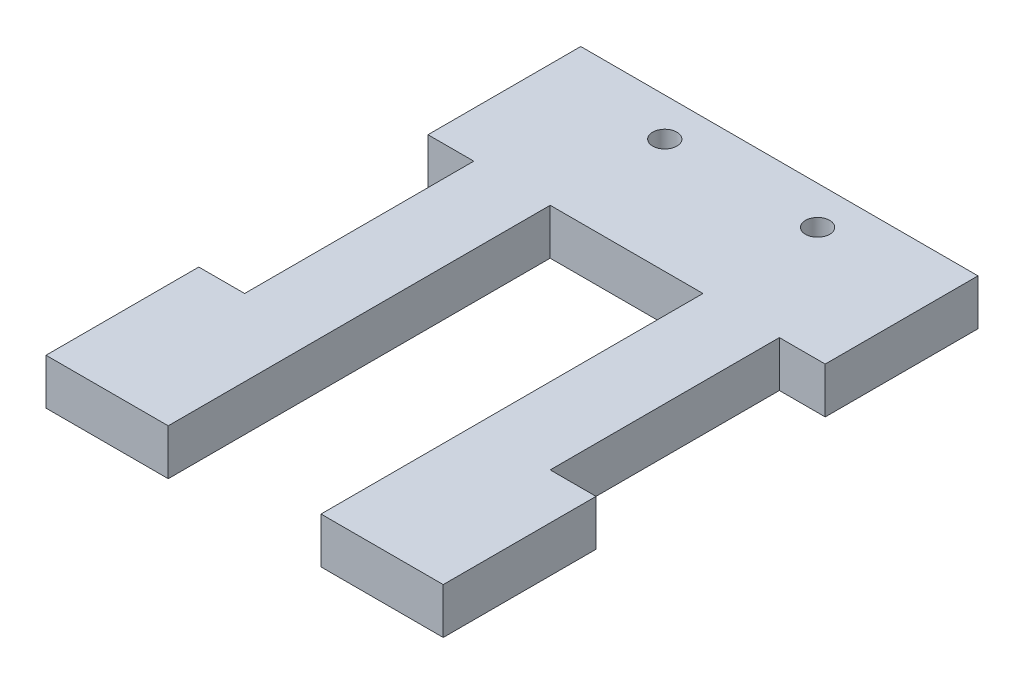
SolidWorks part; units mm, degrees
ref_plane "Front Plane" through (0, 0, 0) normal (0, 0, 1) x (1, 0, 0)
ref_plane "Top Plane" through (0, 0, 0) normal (0, 1, 0) x (1, 0, 0)
ref_plane "Right Plane" through (0, 0, 0) normal (1, 0, 0) x (0, 0, -1)
sketch "Sketch1" plane through (0, 0, 0) normal (0, 1, 0) x (1, 0, 0)
  line L0 (-10, -35) -> (-10, 35)
  line L1 (-20, 35) -> (20, 35)
  line L2 (-20, 35) -> (-20, -35)
  line L3 (-20, -35) -> (20, -35)
  line L4 (20, 35) -> (20, -35)
  line L5 (-20, 35) -> (20, -35) construction
  line L6 (-20, -35) -> (20, 35) construction
  line L7 (10, -35) -> (10, 35)
  line L8 (-20, 15) -> (20, 15)
  line L9 (-20, 0) -> (20, 0) construction
  line L10 (-20, 15) -> (-26, 15)
  line L11 (-20, 15) -> (-20, 35)
  line L12 (-20, 35) -> (-26, 35)
  line L13 (-26, 15) -> (-26, 35)
  line L14 (-26, -15) -> (-26, -35)
  line L15 (-20, -35) -> (-26, -35)
  line L16 (-20, -15) -> (-20, -35)
  line L17 (-20, -15) -> (-26, -15)
  line L18 (0, 35) -> (0, 15)
  line L19 (20, -15) -> (26, -15)
  line L20 (20, -15) -> (20, -35)
  line L21 (20, -35) -> (26, -35)
  line L22 (26, -15) -> (26, -35)
  line L23 (26, 15) -> (26, 35)
  line L24 (20, 35) -> (26, 35)
  line L25 (20, 15) -> (20, 35)
  line L26 (20, 15) -> (26, 15)
  point P0 (0, 0)
  dimension "D1" = 40
  dimension "D2" = 70
  dimension "D3" = 10
  dimension "D4" = 10
  dimension "D5" = 20
  dimension "D6" = 6
extrude "Boss-Extrude1" add sketch "Sketch1" along normal blind 6 contours L8 L7 L3 L4 | L8 L2 L3 L0 | L2 L8 L0 L1 | L0 L8 L7 L1 | L7 L8 L4 L1 | L18 L1 L0 L8 | L13 L10 L2 L12 | L4 L26 L23 L24 | L22 L19 L4 L21 | L2 L17 L14 L15
sketch "Sketch2" plane through (0, 6, 0) normal (0, 1, 0) x (1, 0, 0)
  line L0 (-20, 15) -> (-20, -15) construction
  line L1 (-26, 35) -> (26, 35) construction
  line L2 (0, 35) -> (0, 15) construction
  line L3 (-10, 15) -> (10, 15) construction
  circle A0 centre (-10, 30) radius 1.5875
  circle A1 centre (10, 30) radius 1.5875
  dimension "D1" = 3.175
  dimension "D3" = 5
  dimension "D2" = 10
extrude "Cut-Extrude1" cut sketch "Sketch2" against normal through all
